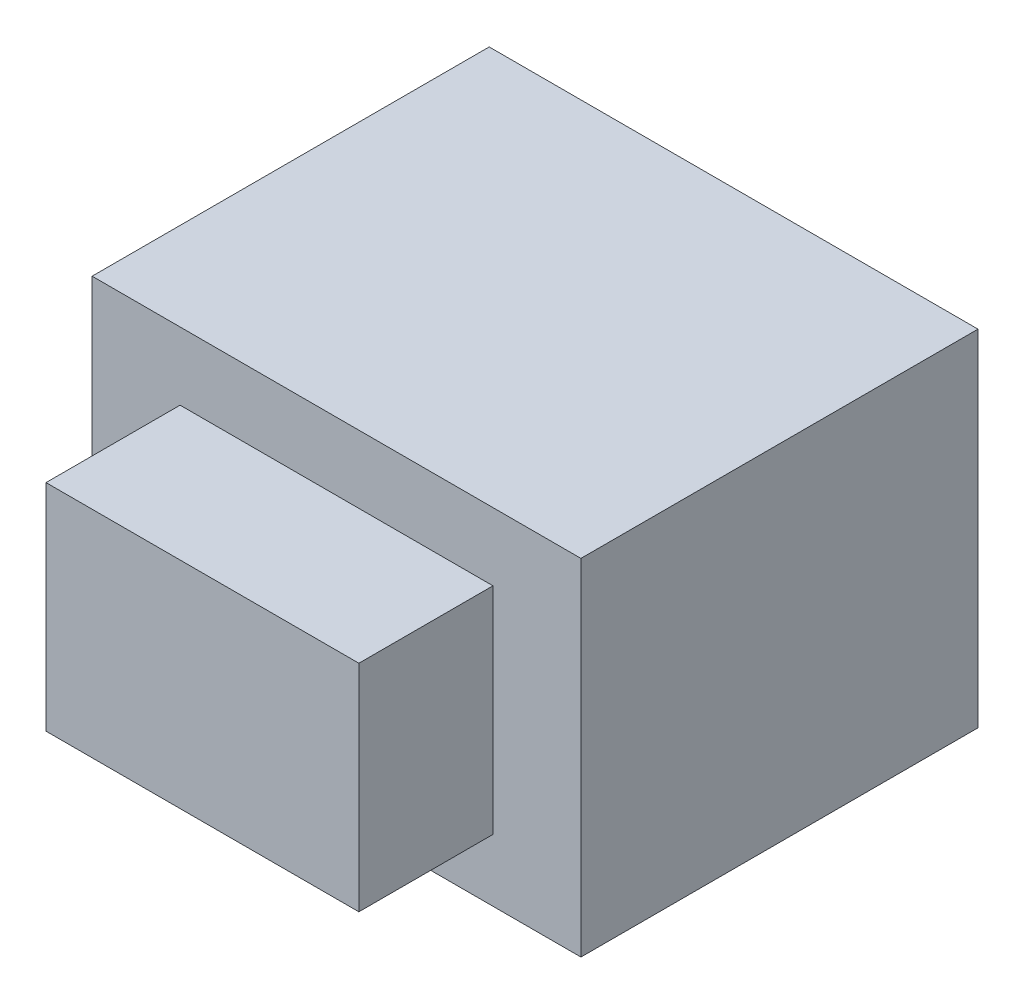
SolidWorks part; units mm, degrees
ref_plane "Front Plane" through (0, 0, 0) normal (0, 0, 1) x (1, 0, 0)
ref_plane "Top Plane" through (0, 0, 0) normal (0, 1, 0) x (1, 0, 0)
ref_plane "Right Plane" through (0, 0, 0) normal (1, 0, 0) x (0, 0, -1)
sketch "Sketch1" plane through (0, 0, 0) normal (0, 1, 0) x (1, 0, 0)
  line L1 (0, 0) -> (36.4531, 0)
  line L2 (0, 0) -> (0, 29.6127)
  line L3 (0, 29.6127) -> (36.4531, 29.6127)
  line L4 (36.4531, 0) -> (36.4531, 29.6127)
extrude "Boss-Extrude1" add sketch "Sketch1" along normal blind 25.7503
sketch "Sketch3" plane through (0, 0, 0) normal (0, 0, 1) x (1, 0, 0)
  line L1 (6.56, 20.699) -> (29.8931, 20.699)
  line L2 (6.56, 20.699) -> (6.56, 4.6431)
  line L3 (6.56, 4.6431) -> (29.8931, 4.6431)
  line L4 (29.8931, 20.699) -> (29.8931, 4.6431)
extrude "Boss-Extrude2" add sketch "Sketch3" along normal blind 10
